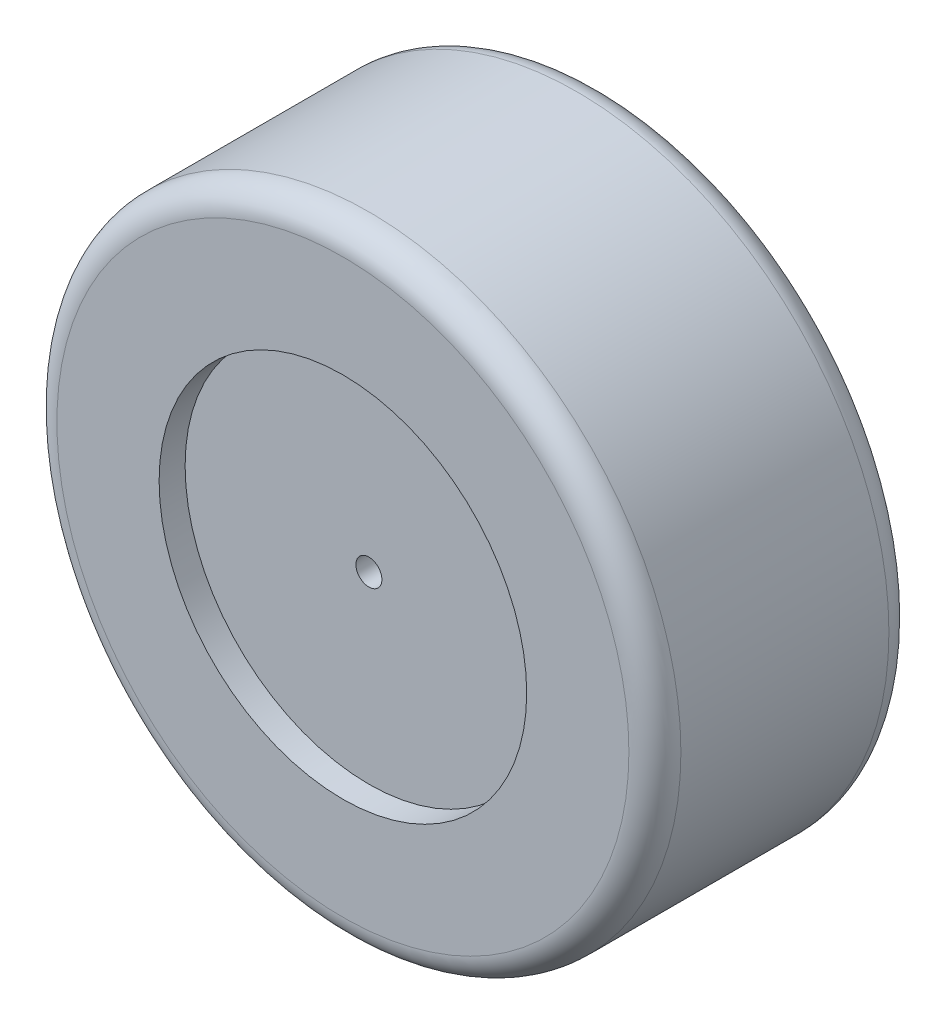
SolidWorks part; units mm, degrees
ref_plane "Front Plane" through (0, 0, 0) normal (0, 0, 1) x (1, 0, 0)
ref_plane "Top Plane" through (0, 0, 0) normal (0, 1, 0) x (1, 0, 0)
ref_plane "Right Plane" through (0, 0, 0) normal (1, 0, 0) x (0, 0, -1)
sketch "Sketch1" plane through (0, 0, 0) normal (0, 0, 1) x (1, 0, 0)
  circle A0 centre (0, 0) radius 60
  dimension "D1" = 120
extrude "Boss-Extrude1" add sketch "Sketch1" along normal blind 50
fillet "Fillet1" radius 5 2 edges at (60, 0, 50) (60, 0, 0)
sketch "Sketch2" plane through (0, 0, 50) normal (0, 0, 1) x (1, 0, 0)
  circle A0 centre (0, 0) radius 35.3445
extrude "Cut-Extrude1" cut sketch "Sketch2" against normal blind 5 contours A0
sketch "Sketch3" plane through (0, 0, 45) normal (0, 0, 1) x (1, 0, 0)
  circle A0 centre (0, 0) radius 2.5
  dimension "D1" = 5
extrude "Cut-Extrude2" cut sketch "Sketch3" against normal through all
